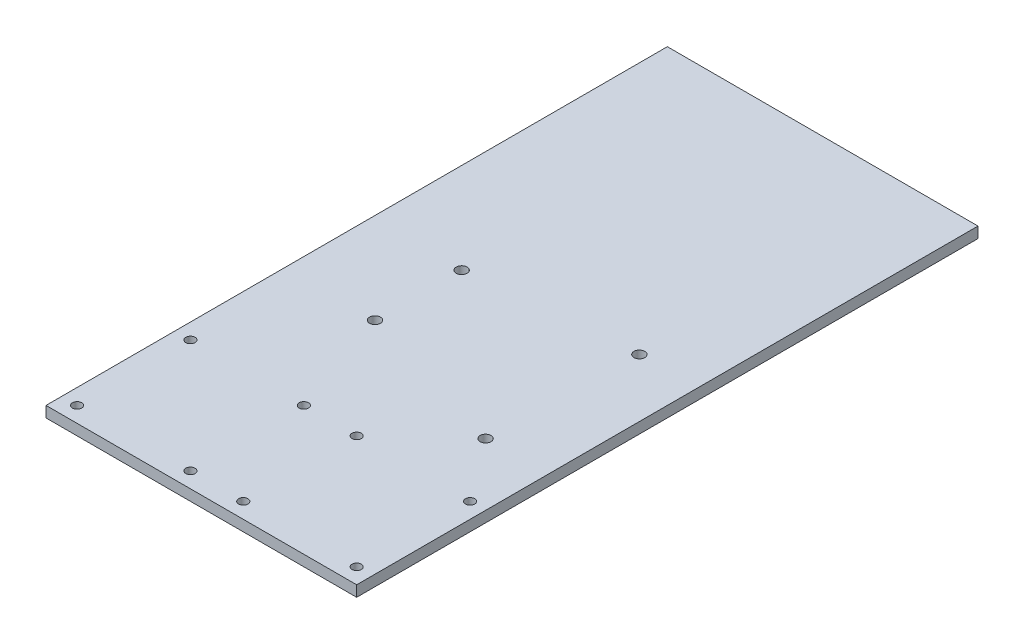
SolidWorks part; units mm, degrees
ref_plane "Front" through (0, 0, 0) normal (0, 0, 1) x (1, 0, 0)
ref_plane "Top" through (0, 0, 0) normal (0, 1, 0) x (1, 0, 0)
ref_plane "Right" through (0, 0, 0) normal (1, 0, 0) x (0, 0, -1)
sketch "Sketch1" plane through (0, 0, 0) normal (0, 1, 0) x (1, 0, 0)
  line L1 (-50, -100) -> (50, -100)
  line L2 (-50, -100) -> (-50, 100)
  line L3 (-50, 100) -> (50, 100)
  line L4 (50, -100) -> (50, 100)
  line L5 (-50, -100) -> (50, 100) construction
  line L6 (-50, 100) -> (50, -100) construction
  point P0 (0, 0)
  dimension "D1" = 100
  dimension "D2" = 200
extrude "Boss-Extrude1" add sketch "Sketch1" along normal blind 3.5
sketch "Sketch4" plane through (0, 3.5, 0) normal (0, 1, 0) x (1, 0, 0)
  line L0 (50, -100) -> (50, 100) construction
  line L1 (-50, -100) -> (50, -100) construction
  circle A0 centre (30, -38.5) radius 1.75
  circle A1 centre (31.3, 9.7) radius 1.75
  circle A2 centre (-20.8, 4.6) radius 1.75
  circle A3 centre (-20.8, -23.3) radius 1.75
  point P8 (-9.0899, 22.0603)
  point P9 (-9.0899, -13.2903)
  point P10 (38.5067, -18.656)
  point P11 (-15.7542, -9.914)
  point P12 (-14.9503, -8.9091)
  point P13 (-19.3715, -6.1961)
  point P14 (-23.7768, 5.8641)
  point P17 (30, -12.176)
  dimension "D6" = 3.5
  dimension "D8" = 61.5
  dimension "D1" = 27.9
  dimension "D2" = 5.1
  dimension "D3" = 50.8
  dimension "D4" = 1.3
  dimension "D5" = 15.2
  dimension "D7" = 20
extrude "Cut-Extrude9" cut sketch "Sketch4" against normal up to next contours A0 | A3 | A2 | A1
sketch "Sketch2" plane through (0, 3.5, 0) normal (0, 1, 0) x (1, 0, 0)
  line L0 (-50, 100) -> (-50, -100) construction
  circle A0 centre (-45, -58.5) radius 1.5
  circle A1 centre (-45, -95) radius 1.5
  circle A2 centre (-8.5, -58.5) radius 1.5
  circle A3 centre (-8.5, -95) radius 1.5
  dimension "D1" = 3
  dimension "D2" = 36.5
  dimension "D3" = 36.5
  dimension "D4" = 5
  dimension "D5" = 5
extrude "Cut-Extrude10" cut sketch "Sketch2" against normal up to next
mirror "Mirror2" about plane through (0, 0, 0) normal (1, 0, 0) of "Cut-Extrude10"
sketch "Sketch8" plane through (0, 3.5, 0) normal (0, 1, 0) x (1, 0, 0)
  line L0 (-50, 100) -> (-50, -100) construction
  line L1 (-37.5, -80.2265) -> (-42.5, -83.1132)
  line L2 (-42.5, -83.1132) -> (-42.5, -88.8868)
  line L3 (-42.5, -88.8868) -> (-37.5, -91.7735)
  line L4 (-37.5, -91.7735) -> (-32.5, -88.8868)
  line L5 (-32.5, -88.8868) -> (-32.5, -83.1132)
  line L6 (-32.5, -83.1132) -> (-37.5, -80.2265)
  line L7 (-50, -100) -> (50, -100) construction
  circle A0 centre (-37.5, -86) radius 5 construction
  point P10 (0, 0)
  point P12 (-86.5735, -72.4711)
  dimension "D3" = 10
  dimension "D1" = 12.5
  dimension "D2" = 14
extrude "Cut-Extrude6" [suppressed] cut sketch "Sketch8" against normal up to next
pattern_linear "LPattern8" [suppressed] count 7 spacing 12.5 count 9 spacing 21.5
sketch "Sketch9" [suppressed] plane through (0, 3.5, 0) normal (0, 1, 0) x (1, 0, 0)
  line L0 (-35, -68.8301) -> (-27.5, -81.6699) construction
  line L1 (-37.5, -70.2735) -> (-32.5, -67.3868) construction
  line L2 (-25, -80.2265) -> (-30, -83.1132) construction
  line L3 (-30, -67.3868) -> (-25, -70.2735) construction
  line L7 (-26.25, -72.3632) -> (-31.25, -69.4765)
  line L8 (-31.25, -69.4765) -> (-36.25, -72.3632)
  line L9 (-36.25, -72.3632) -> (-36.25, -78.1368)
  line L10 (-36.25, -78.1368) -> (-31.25, -81.0235)
  line L11 (-31.25, -81.0235) -> (-26.25, -78.1368)
  line L12 (-26.25, -78.1368) -> (-26.25, -72.3632)
  circle A0 centre (-31.25, -75.25) radius 5 construction
  dimension "D1" = 10
extrude "Cut-Extrude7" [suppressed] cut sketch "Sketch9" against normal up to next
pattern_linear "LPattern9" [suppressed] count 6 spacing 12.5 count 8 spacing 21.5
